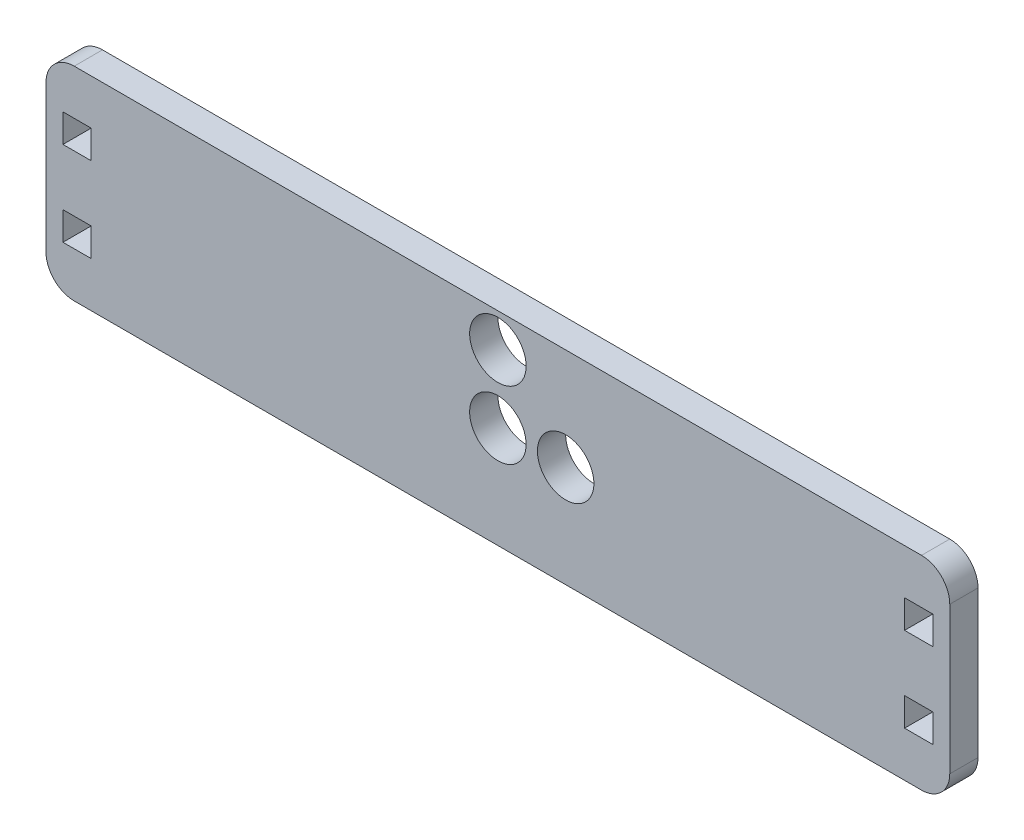
SolidWorks part; units mm, degrees
ref_plane "Plan de face" through (0, 0, 0) normal (0, 0, 1) x (1, 0, 0)
ref_plane "Plan de dessus" through (0, 0, 0) normal (0, 1, 0) x (1, 0, 0)
ref_plane "Plan de droite" through (0, 0, 0) normal (1, 0, 0) x (0, 0, -1)
sketch "Esquisse1" plane through (0, 0, 0) normal (0, 0, 1) x (1, 0, 0)
  line L0 (-80, 18) -> (80, 18)
  line L1 (80, 18) -> (80, -18)
  line L2 (80, -18) -> (-80, -18)
  line L3 (-80, -18) -> (-80, 18)
  line L4 (0, 0) -> (0, 35.7778) construction
  line L5 (0, 0) -> (80, 0) construction
  circle A0 centre (0, 0) radius 5
  circle A1 centre (12, 0) radius 5
  circle A2 centre (0, 12) radius 5
  line B0 (77, 5) -> (77, 10)
  line B1 (77, 5) -> (72, 5)
  line B2 (72, 5) -> (72, 10)
  line B3 (77, 10) -> (72, 10)
  line B4 (77, -5) -> (77, -10)
  line B5 (77, -5) -> (72, -5)
  line B6 (72, -5) -> (72, -10)
  line B7 (77, -10) -> (72, -10)
  line B8 (74.5, 0) -> (81.4724, 0) construction
  circle B9 centre (74.5, 0) radius 2 construction
  line B10 (-77, 5) -> (-77, 10)
  line B11 (-77, 5) -> (-72, 5)
  line B12 (-72, 5) -> (-72, 10)
  line B13 (-77, 10) -> (-72, 10)
  line B14 (-77, -5) -> (-77, -10)
  line B15 (-77, -5) -> (-72, -5)
  line B16 (-72, -5) -> (-72, -10)
  line B17 (-77, -10) -> (-72, -10)
  dimension "D4" = 10
  dimension "D5" = 10
  dimension "D7" = 10
  dimension "D1" = 160
  dimension "D2" = 144
  dimension "D3" = 36
  dimension "D6" = 12
  dimension "D8" = 12
sketch_block_instance "Trou M4 plots 5mm-1"
sketch_block "Trou M4 plots 5mm" parameters "D2"=4, "D5"=4, "D1"=5, "D3"=5, "D4"=10
sketch_block_instance "Trou M4 plots 5mm-3"
extrude "Boss.-Extru.1" add sketch "Esquisse1" along normal blind 5
fillet "Congé1" radius 5 4 edges at (80, -18, 2.5) (80, 18, 2.5) (-80, -18, 2.5) (-80, 18, 2.5)
